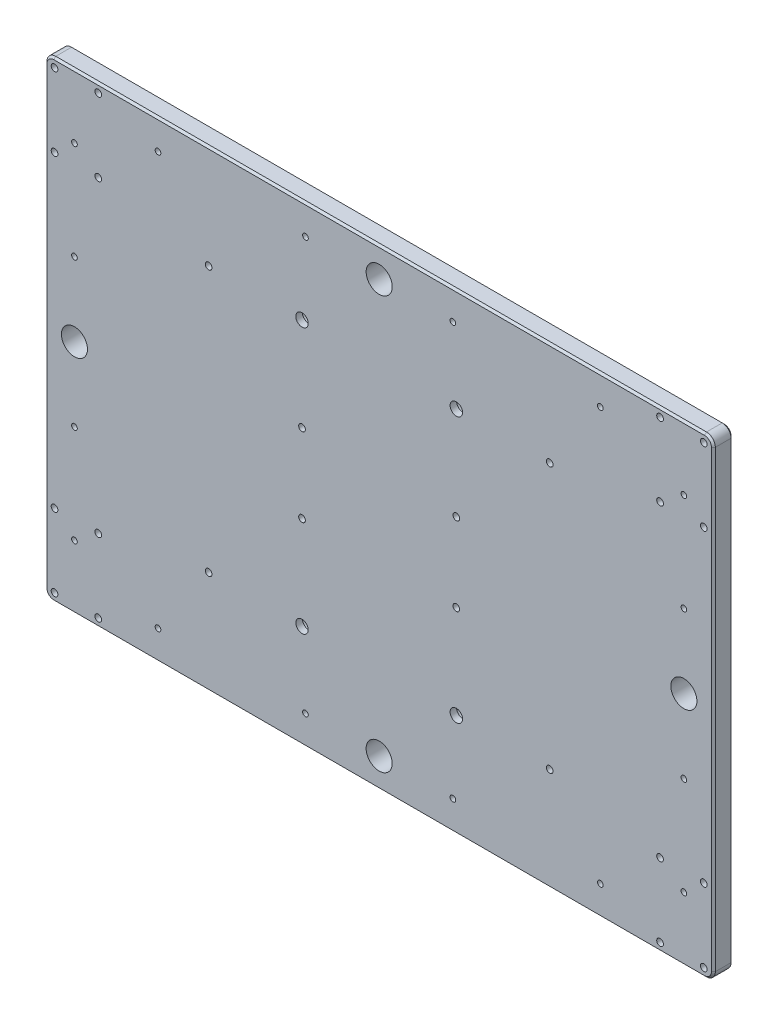
SolidWorks part; units mm, degrees
material "AL6061"
ref_plane "前视基准面" through (0, 0, 0) normal (0, 0, 1) x (1, 0, 0)
ref_plane "上视基准面" through (0, 0, 0) normal (0, 1, 0) x (1, 0, 0)
ref_plane "右视基准面" through (0, 0, 0) normal (1, 0, 0) x (0, 0, -1)
sketch "草图1" plane through (0, 0, 0) normal (0, 0, 1) x (1, 0, 0)
  line L1 (-340, 240) -> (340, 240)
  line L2 (-340, 240) -> (-340, -240)
  line L3 (-340, -240) -> (340, -240)
  line L4 (340, 240) -> (340, -240)
  line L5 (-340, 240) -> (340, -240) construction
  line L6 (-340, -240) -> (340, 240) construction
  point P0 (0, 0)
  dimension "D1" = 680
  dimension "D2" = 480
extrude "凸台-拉伸1" add sketch "草图1" along normal blind 20
fillet "圆角1" radius 9 4 edges at (-340, 240, 10) (340, 240, 10) (340, -240, 10) (-340, -240, 10)
chamfer "倒角3" distance 2 angle 45 16 edges at (-337.364, -237.364, 0) (0, -240, 0) (337.364, -237.364, 0) (340, 0, 0) (337.364, 237.364, 0) (0, 240, 0) (-337.364, 237.364, 0) (-340, 0, 0) (337.364, 237.364, 20) (340, 0, 20) (337.364, -237.364, 20) (0, -240, 20) (-337.364, -237.364, 20) (-340, 0, 20) (-337.364, 237.364, 20) (0, 240, 20)
hole_wizard "M30 螺纹孔1" positions "草图4" profile "草图5" tap size "M30" standard "GB"
sketch "草图4" plane through (0, 0, 0) normal (0, 0, -1) x (-1, 0, 0)
  line L1 (-310, 210) -> (310, 210) construction
  line L2 (-310, 210) -> (-310, -210) construction
  line L3 (-310, -210) -> (310, -210) construction
  line L4 (310, 210) -> (310, -210) construction
  line L5 (-310, 210) -> (310, -210) construction
  line L6 (-310, -210) -> (310, 210) construction
  line L7 (-331, 240) -> (331, 240) construction
  line L8 (-340, -231) -> (-340, 231) construction
  point P0 (0, 210)
  point P2 (-310, 0)
  point P4 (0, -210)
  point P6 (310, 0)
  point P101 (0, 0)
  dimension "D1" = 30
  dimension "D2" = 30
sketch "草图5" plane through (0, 210, 0) normal (1, 0, 0) x (0, 1, 0)
  line L0 (0, 0) -> (0, 78.4614)
  line L1 (0, 78.4614) -> (13.25, 70.5)
  line L2 (13.25, 70.5) -> (13.25, 0)
  line L5 (13.25, 0) -> (0, 0)
  line L10 (0, 78.4614) -> (-13.25, 70.5) construction
  line L11 (0, -6.35) -> (0, 107.95) construction
  dimension "螺纹孔钻头直径" = 26.5
  dimension "螺纹孔钻头深度" = 70.5
  dimension "导头角度" = 118
cosmetic thread "孔螺蚊线1" parameters "D1"=60, "D2"=30
cosmetic thread "孔螺蚊线2" parameters "D1"=60, "D2"=30
cosmetic thread "孔螺蚊线3" parameters "D1"=60, "D2"=30
cosmetic thread "孔螺蚊线4" parameters "D1"=60, "D2"=30
sketch "草图16" plane through (0, 0, 0) normal (0, 0, -1) x (-1, 0, 0)
  line L1 (330.25, -231.25) -> (285.75, -231.25) construction
  line L2 (330.25, -231.25) -> (330.25, -156.75) construction
  line L3 (330.25, -156.75) -> (285.75, -156.75) construction
  line L4 (285.75, -231.25) -> (285.75, -156.75) construction
  line L5 (330.25, -231.25) -> (285.75, -156.75) construction
  line L6 (330.25, -156.75) -> (285.75, -231.25) construction
  line L7 (-330.25, -231.25) -> (-285.75, -231.25) construction
  line L8 (-330.25, -231.25) -> (-330.25, -156.75) construction
  line L9 (-330.25, -156.75) -> (-285.75, -156.75) construction
  line L10 (-285.75, -231.25) -> (-285.75, -156.75) construction
  line L11 (-330.25, -231.25) -> (-285.75, -156.75) construction
  line L12 (-330.25, -156.75) -> (-285.75, -231.25) construction
  line L13 (330.25, 231.25) -> (285.75, 231.25) construction
  line L14 (330.25, 231.25) -> (330.25, 156.75) construction
  line L15 (330.25, 156.75) -> (285.75, 156.75) construction
  line L16 (285.75, 231.25) -> (285.75, 156.75) construction
  line L17 (330.25, 231.25) -> (285.75, 156.75) construction
  line L18 (330.25, 156.75) -> (285.75, 231.25) construction
  line L19 (-330.25, 231.25) -> (-285.75, 231.25) construction
  line L20 (-330.25, 231.25) -> (-330.25, 156.75) construction
  line L21 (-330.25, 156.75) -> (-285.75, 156.75) construction
  line L22 (-285.75, 231.25) -> (-285.75, 156.75) construction
  line L23 (-330.25, 231.25) -> (-285.75, 156.75) construction
  line L24 (-330.25, 156.75) -> (-285.75, 231.25) construction
  circle A0 centre (308, 194) radius 27 construction
  circle A1 centre (-308, 194) radius 27 construction
  circle A2 centre (-308, -194) radius 27 construction
  circle A3 centre (308, -194) radius 27 construction
  circle A4 centre (308, 194) radius 27 construction
  circle A5 centre (-308, 194) radius 27 construction
  circle A6 centre (-308, -194) radius 27 construction
  circle A7 centre (308, -194) radius 27 construction
  dimension "D1" = 44.5
  dimension "D2" = 74.5
hole_wizard "M8 螺纹孔1" positions "草图17" profile "草图18" tap size "M8" standard "GB" end condition through all
sketch "草图17" plane through (0, 0, 0) normal (0, 0, -1) x (-1, 0, 0)
  line L0 (-285.75, -231.25) -> (-285.75, -156.75) construction
  point P0 (330.25, -231.25)
  point P3 (285.75, -231.25)
  point P6 (285.75, -156.75)
  point P9 (330.25, -156.75)
  point P12 (-285.75, -231.25)
  point P16 (-330.25, -231.25)
  point P19 (-330.25, -156.75)
  point P22 (-285.75, -156.75)
  point P28 (330.25, 156.75)
  point P31 (285.75, 156.75)
  point P34 (285.75, 231.25)
  point P37 (330.25, 231.25)
  point P40 (-285.75, 156.75)
  point P43 (-330.25, 156.75)
  point P46 (-330.25, 231.25)
  point P49 (-285.75, 231.25)
cosmetic thread "孔螺蚊线21" parameters "D2"=8
cosmetic thread "孔螺蚊线22" parameters "D2"=8
cosmetic thread "孔螺蚊线23" parameters "D2"=8
cosmetic thread "孔螺蚊线24" parameters "D2"=8
cosmetic thread "孔螺蚊线25" parameters "D2"=8
cosmetic thread "孔螺蚊线26" parameters "D2"=8
cosmetic thread "孔螺蚊线27" parameters "D2"=8
cosmetic thread "孔螺蚊线28" parameters "D2"=8
cosmetic thread "孔螺蚊线29" parameters "D2"=8
cosmetic thread "孔螺蚊线30" parameters "D2"=8
cosmetic thread "孔螺蚊线31" parameters "D2"=8
cosmetic thread "孔螺蚊线32" parameters "D2"=8
cosmetic thread "孔螺蚊线33" parameters "D2"=8
cosmetic thread "孔螺蚊线34" parameters "D2"=8
cosmetic thread "孔螺蚊线35" parameters "D2"=8
cosmetic thread "孔螺蚊线36" parameters "D2"=8
sketch "草图18" plane through (-330.25, -231.25, 0) normal (1, 0, 0) x (0, 1, 0)
  line L0 (0, 0) -> (0, 20)
  line L1 (0, 20) -> (3.4, 20)
  line L2 (3.4, 20) -> (3.4, 0)
  line L5 (3.4, 0) -> (0, 0)
  line L11 (0, -6.35) -> (0, 107.95) construction
  dimension "通孔螺纹孔钻头直径" = 6.8
  dimension "通孔螺纹孔钻头深度" = 20
hole_wizard "打孔尺寸(%根据)内六角圆柱头螺钉的类型2" positions "草图19" profile "草图20" counterbore size "M6" standard "GB"
sketch "草图19" plane through (0, 0, 0) normal (0, 0, -1) x (-1, 0, 0)
  line L0 (0, -240) -> (0, -210) construction
  line L1 (331, -240) -> (-331, -240) construction
  line L3 (75, -210) -> (-75, -210) construction
  line L5 (225, -210) -> (-225, -210) construction
  line L7 (0, 240) -> (0, 210) construction
  line L8 (-331, 240) -> (331, 240) construction
  line L10 (75, 210) -> (-75, 210) construction
  line L12 (225, 210) -> (-225, 210) construction
  line L14 (340, 0) -> (310, 0) construction
  line L15 (340, 231) -> (340, -231) construction
  line L17 (310, -75) -> (310, 75) construction
  line L19 (310, -175) -> (310, 175) construction
  line L20 (-340, 0) -> (-310, 0) construction
  line L21 (-340, -231) -> (-340, 231) construction
  line L23 (-310, -75) -> (-310, 75) construction
  line L25 (-310, -175) -> (-310, 175) construction
  point P0 (225, -210)
  point P2 (75, -210)
  point P4 (-75, -210)
  point P6 (-225, -210)
  point P8 (225, 210)
  point P10 (75, 210)
  point P12 (-75, 210)
  point P14 (-225, 210)
  point P17 (310, -175)
  point P19 (310, 175)
  point P21 (-310, -175)
  point P23 (-310, 175)
  point P35 (0, -210)
  point P43 (0, -210)
  point P55 (0, 210)
  point P61 (0, 210)
  point P77 (310, 0)
  point P82 (310, 0)
  point P95 (-310, 0)
  point P100 (-310, 0)
  point P105 (-310, -75)
  point P108 (-310, 75)
  point P112 (310, -75)
  point P115 (310, 75)
  dimension "D1" = 30
  dimension "D2" = 150
  dimension "D3" = 150
  dimension "D4" = 30
  dimension "D5" = 150
  dimension "D6" = 150
  dimension "D7" = 150
  dimension "D8" = 30
  dimension "D9" = 100
  dimension "D10" = 30
  dimension "D11" = 100
sketch "草图20" plane through (-225, -210, 0) normal (1, 0, 0) x (0, 1, 0)
  line L0 (0, 0) -> (0, 21.7328)
  line L1 (0, 21.7328) -> (3.3, 19.75)
  line L2 (3.3, 19.75) -> (3.3, 6.8)
  line L3 (3.3, 6.8) -> (5.5, 6.8)
  line L4 (5.5, 6.8) -> (5.5, 0)
  line L5 (5.5, 0) -> (0, 0)
  line L10 (0, 21.7328) -> (-3.3, 19.75) construction
  line L11 (0, -6.35) -> (0, 107.95) construction
  dimension "孔直径" = 6.6
  dimension "孔深度" = 19.75
  dimension "柱形沉头孔直径" = 11
  dimension "柱形沉头孔深度" = 6.8
  dimension "导头角度" = 118
hole_wizard "打孔尺寸(%根据)内六角圆柱头螺钉的类型3" positions "草图21" profile "草图22" counterbore size "M12" standard "GB"
sketch "草图21" plane through (0, 0, 0) normal (0, 0, -1) x (-1, 0, 0)
  point P0 (78.5, -135)
  point P3 (-78.5, -135)
  point P6 (-78.5, 135)
  point P9 (78.5, 135)
sketch "草图22" plane through (-78.5, -135, 0) normal (1, 0, 0) x (0, 1, 0)
  line L0 (0, 0) -> (0, 23.8058)
  line L1 (0, 23.8058) -> (6.75, 19.75)
  line L2 (6.75, 19.75) -> (6.75, 13)
  line L3 (6.75, 13) -> (10, 13)
  line L4 (10, 13) -> (10, 0)
  line L5 (10, 0) -> (0, 0)
  line L10 (0, 23.8058) -> (-6.75, 19.75) construction
  line L11 (0, -6.35) -> (0, 107.95) construction
  dimension "孔直径" = 13.5
  dimension "孔深度" = 19.75
  dimension "柱形沉头孔直径" = 20
  dimension "柱形沉头孔深度" = 13
  dimension "导头角度" = 118
hole_wizard "M8 螺纹孔2" positions "草图23" profile "草图25" tap size "M8" standard "GB" end condition through all
sketch "草图23" plane through (0, 0, 20) normal (0, 0, 1) x (1, 0, 0)
  point P0 (-173.5, 135)
  point P4 (-78.5, 40)
  point P7 (173.5, 135)
  point P10 (78.5, 40)
  point P13 (78.5, -40)
  point P16 (-78.5, -40)
  point P19 (-173.5, -135)
  point P22 (173.5, -135)
sketch "草图25" plane through (-173.5, 135, 20) normal (1, 0, 0) x (0, -1, 0)
  line L0 (0, 0) -> (0, 20)
  line L1 (0, 20) -> (3.4, 20)
  line L2 (3.4, 20) -> (3.4, 0)
  line L5 (3.4, 0) -> (0, 0)
  line L11 (0, -6.35) -> (0, 107.95) construction
  dimension "通孔螺纹孔钻头直径" = 6.8
  dimension "通孔螺纹孔钻头深度" = 20
cosmetic thread "孔螺蚊线37" parameters "D2"=8
cosmetic thread "孔螺蚊线38" parameters "D2"=8
cosmetic thread "孔螺蚊线39" parameters "D2"=8
cosmetic thread "孔螺蚊线40" parameters "D2"=8
cosmetic thread "孔螺蚊线41" parameters "D2"=8
cosmetic thread "孔螺蚊线42" parameters "D2"=8
cosmetic thread "孔螺蚊线43" parameters "D2"=8
cosmetic thread "孔螺蚊线44" parameters "D2"=8
